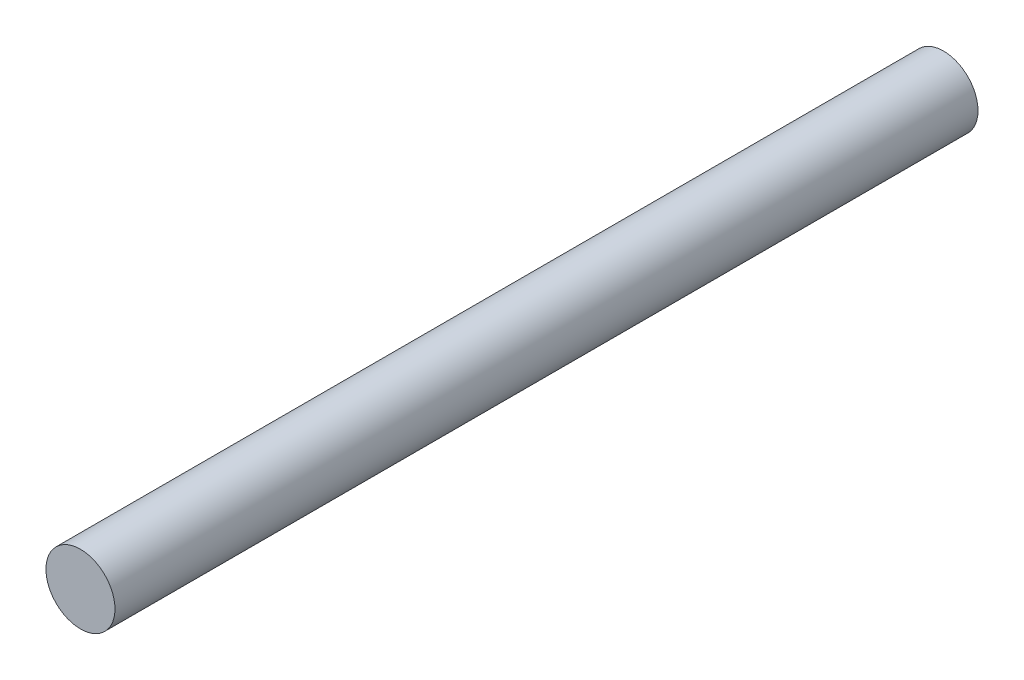
SolidWorks part; units mm, degrees
material "2024-T361"
ref_plane "Front Plane" through (0, 0, 0) normal (0, 0, 1) x (1, 0, 0)
ref_plane "Top Plane" through (0, 0, 0) normal (0, 1, 0) x (1, 0, 0)
ref_plane "Right Plane" through (0, 0, 0) normal (1, 0, 0) x (0, 0, -1)
sketch "Sketch1" plane through (0, 0, 0) normal (0, 0, 1) x (1, 0, 0)
  circle A0 centre (-171.6005, 12.5) radius 4.2
extrude "Boss-Extrude1" add sketch "Sketch1" along normal blind 80 and the other way blind 25
